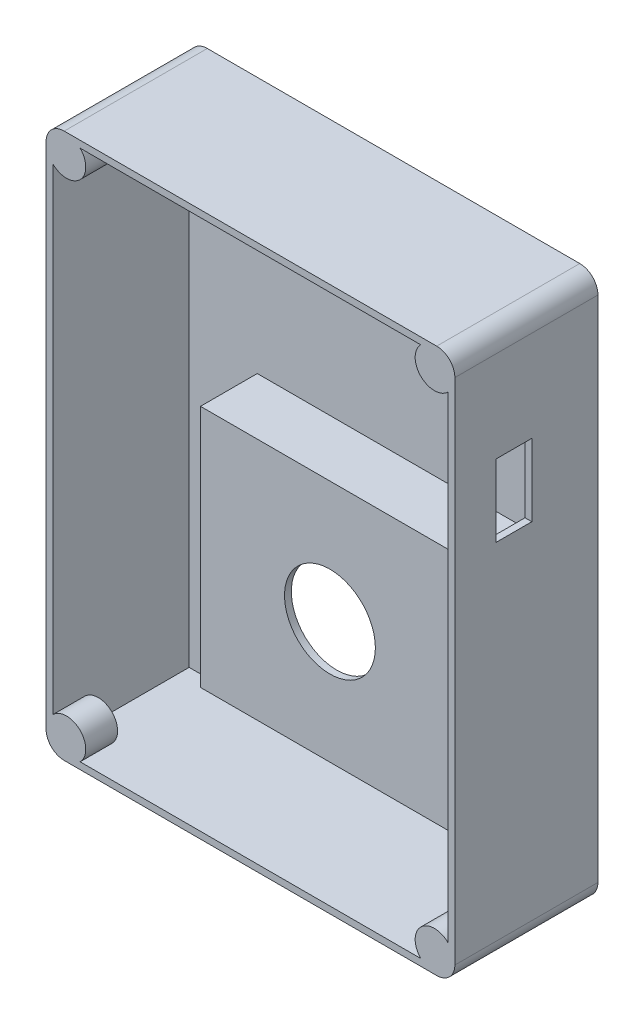
SolidWorks part; units mm, degrees
ref_plane "Front Plane" through (0, 0, 0) normal (0, 0, 1) x (1, 0, 0)
ref_plane "Top Plane" through (0, 0, 0) normal (0, 1, 0) x (1, 0, 0)
ref_plane "Right Plane" through (0, 0, 0) normal (1, 0, 0) x (0, 0, -1)
sketch "Sketch2" plane through (0, 0, 0) normal (0, 0, 1) x (1, 0, 0)
  line L1 (-45, -60) -> (45, -60)
  line L2 (-45, -60) -> (-45, 60)
  line L3 (-45, 60) -> (45, 60)
  line L4 (45, -60) -> (45, 60)
  line L5 (-45, -60) -> (45, 60) construction
  line L6 (-45, 60) -> (45, -60) construction
  point P0 (0, 0)
extrude "Boss-Extrude1" add sketch "Sketch2" along normal blind 31.5
sketch "Sketch4" plane through (0, 0, 31.5) normal (0, 0, 1) x (1, 0, 0)
  line L1 (-43.5, -58.5) -> (43.5, -58.5)
  line L2 (-43.5, -58.5) -> (-43.5, 58.5)
  line L3 (-43.5, 58.5) -> (43.5, 58.5)
  line L4 (43.5, -58.5) -> (43.5, 58.5)
  line L5 (-43.5, -58.5) -> (43.5, 58.5) construction
  line L6 (-43.5, 58.5) -> (43.5, -58.5) construction
  point P0 (0, 0)
extrude "Cut-Extrude1" cut sketch "Sketch4" against normal blind 30
fillet "Fillet4" radius 4 4 edges at (45, -60, 15.75) (-45, -60, 15.75) (45, 60, 15.75) (-45, 60, 15.75)
ref_plane "Plane1" through (0, 0, 0) normal (1, 0, 0) x (0, 0, -1)
ref_plane "Plane2" through (0, 0, 0) normal (0, 1, 0) x (1, 0, 0)
sketch "Sketch18" plane through (0, 0, 1.5) normal (0, 0, 1) x (1, 0, 0)
  line L0 (0, -58.5) -> (0, -48.5)
  line L1 (-43.5, -58.5) -> (43.5, -58.5) construction
  line L2 (0, -16.5) -> (0, 16.5) construction
  line L3 (0, -48.5) -> (0, -21.7755)
  line L5 (-28.5, -48.5755) -> (28.5, -48.5755)
  line L6 (-28.5, -48.5755) -> (-28.5, 5.0245)
  line L7 (-28.5, 5.0245) -> (28.5, 5.0245)
  line L8 (28.5, -48.5755) -> (28.5, 5.0245)
  line L9 (-28.5, -48.5755) -> (28.5, 5.0245) construction
  line L10 (-28.5, 5.0245) -> (28.5, -48.5755) construction
extrude "khay_pin" add sketch "Sketch18" along normal blind 12.5
sketch "Sketch21" plane through (0, 0, 14) normal (0, 0, 1) x (1, 0, 0)
  line L0 (-28.5, -21.7755) -> (28.5, -21.7755) construction
  line L1 (-28.5, -48.5755) -> (-28.5, 5.0245) construction
  line L2 (28.5, -48.5755) -> (28.5, 5.0245) construction
  line L4 (-26.5, -46.5755) -> (26.5, -46.5755)
  line L5 (-26.5, -46.5755) -> (-26.5, 3.0245)
  line L6 (-26.5, 3.0245) -> (26.5, 3.0245)
  line L7 (26.5, -46.5755) -> (26.5, 3.0245)
  line L8 (-26.5, -46.5755) -> (26.5, 3.0245) construction
  line L9 (-26.5, 3.0245) -> (26.5, -46.5755) construction
  point P6 (0, -21.7755)
extrude "Boss-Extrude11" add sketch "Sketch21" against normal blind 15
sketch "Sketch22" plane through (0, 0, -1) normal (0, 0, -1) x (-1, 0, 0)
  line L0 (-26.5, -21.7755) -> (26.5, -21.7755) construction
  line L1 (-26.5, -46.5755) -> (-26.5, 3.0245) construction
  line L2 (26.5, 3.0245) -> (26.5, -46.5755) construction
  line L4 (-26.5, -46.5755) -> (26.5, -46.5755)
  line L5 (-26.5, -46.5755) -> (-26.5, 3.0245)
  line L6 (-26.5, 3.0245) -> (26.5, 3.0245)
  line L7 (26.5, -46.5755) -> (26.5, 3.0245)
  line L8 (-26.5, -46.5755) -> (26.5, 3.0245) construction
  line L9 (-26.5, 3.0245) -> (26.5, -46.5755) construction
  point P6 (0, -21.7755)
extrude "Cut-Extrude4" cut sketch "Sketch22" against normal blind 13.5
sketch "Sketch30" plane through (26.5, 0, 0) normal (-1, 0, 0) x (0, 0, 1)
  line L0 (0, 3.0245) -> (12.5, 3.0245)
  line L1 (12.5, 3.0245) -> (12.5, -1.9755)
  line L2 (12.5, -1.9755) -> (12.5, -15.9755)
  line L3 (12.5, -1.9755) -> (5.5, -1.9755)
  line L4 (12.5, -15.9755) -> (5.5, -15.9755)
  line L5 (5.5, -1.9755) -> (5.5, -15.9755)
  line L6 (12.5, 3.0245) -> (12.5, -46.5755) construction
  line M3 (12.5, -46.5755) -> (12.5, 3.0245)
extrude "Cut-Extrude8" cut sketch "Sketch30" against normal blind 5 contours L3 L5 L4 M3
sketch "Sketch34" plane through (0, 0, 31.5) normal (0, 0, 1) x (1, 0, 0)
  line L0 (-43.5, 58.5) -> (-40.5, 58.5)
  line L1 (43.5, 58.5) -> (-43.5, 58.5) construction
  line L2 (-40.5, 58.5) -> (-40.5, 55.5)
  circle A0 centre (-40.5, 55.5) radius 4.2426
extrude "Boss-Extrude12" add sketch "Sketch34" against normal blind 7
sketch "Sketch37" plane through (45, 0, 0) normal (1, 0, 0) x (0, 0, -1)
  line L0 (-31.5, 56) -> (-31.5, 28)
  line L1 (-31.5, -56) -> (-31.5, 56) construction
  line L2 (-31.5, 28) -> (-18.5, 28)
  line L4 (-22.45, 20.05) -> (-14.55, 20.05)
  line L5 (-22.45, 20.05) -> (-22.45, 35.95)
  line L6 (-22.45, 35.95) -> (-14.55, 35.95)
  line L7 (-14.55, 20.05) -> (-14.55, 35.95)
  line L8 (-22.45, 20.05) -> (-14.55, 35.95) construction
  line L9 (-22.45, 35.95) -> (-14.55, 20.05) construction
extrude "Cut-Extrude10" cut sketch "Sketch37" against normal blind 5
mirror "Mirror1" about plane through (0, 0, 0) normal (1, 0, 0) of "Boss-Extrude12"
mirror "Mirror2" about plane through (0, 0, 0) normal (0, 1, 0) of "Mirror1", "Boss-Extrude12"
sketch "Sketch38" plane through (0, 0, 14) normal (0, 0, 1) x (1, 0, 0)
  line L0 (0, 5.0245) -> (0, -21.7755)
  line L1 (-28.5, 5.0245) -> (28.5, 5.0245) construction
  line L2 (0, -16.5) -> (0, 16.5) construction
  circle A0 centre (0, -21.7755) radius 10
extrude "Cut-Extrude11" cut sketch "Sketch38" against normal blind 10
